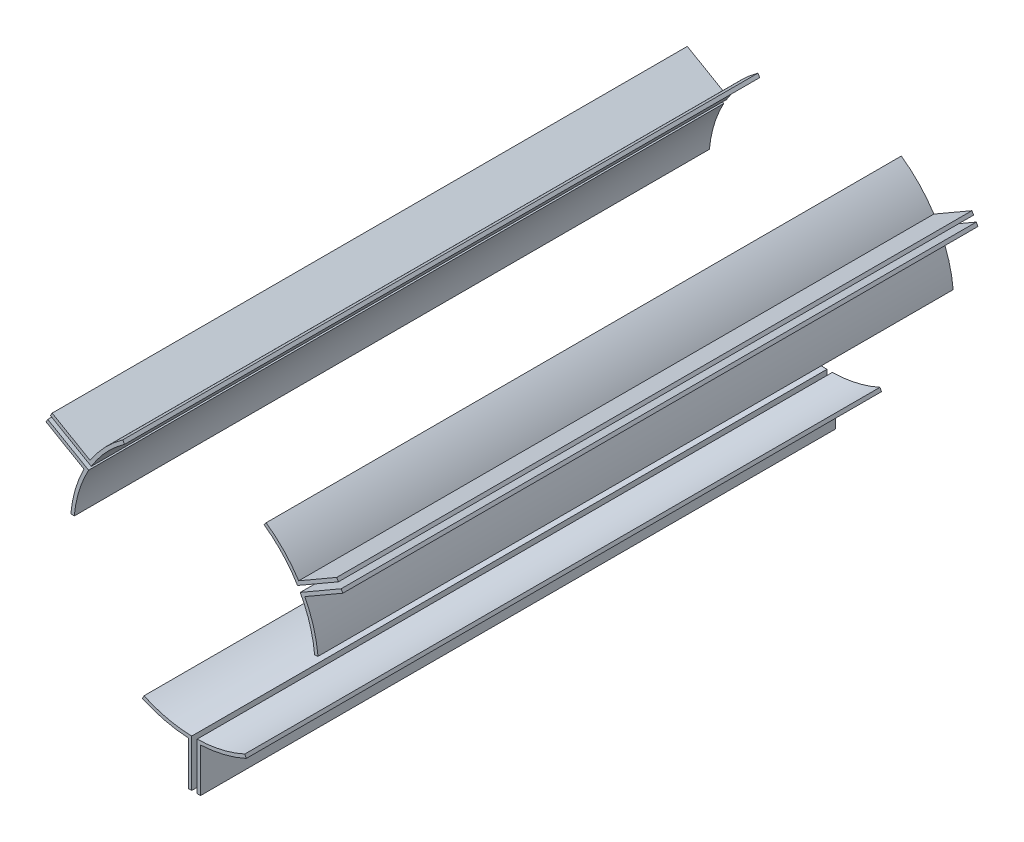
SolidWorks part; units mm, degrees
ref_plane "Front Plane" through (0, 0, 0) normal (0, 0, 1) x (1, 0, 0)
ref_plane "Top Plane" through (0, 0, 0) normal (0, 1, 0) x (1, 0, 0)
ref_plane "Right Plane" through (0, 0, 0) normal (1, 0, 0) x (0, 0, -1)
sketch "Sketch1" plane through (0, 0, 0) normal (0, 0, 1) x (1, 0, 0)
  line L0 (0, 0) -> (0, 104.0303) construction
  line L4 (0, 0) -> (35.2831, 76.7317) construction
  line L10 (0, 0) -> (129.8857, -74.9895) construction
  line L11 (0, 0) -> (-129.8857, -74.9895) construction
  line L28 (55, 0) -> (-55, 0) construction
  line L29 (0, 0) -> (0, -104.0303) construction
  line L30 (0, 0) -> (129.8857, 74.9895) construction
  line L31 (0, 0) -> (-129.8857, 74.9895) construction
  line L32 (-1.8796, -84.4341) -> (-1.8796, -117.4541)
  line L33 (-1.8796, -117.4541) -> (-4.2926, -117.4541)
  line L34 (-4.2926, -117.4541) -> (-4.2926, -86.7619)
  line L35 (-35.2831, -76.7317) -> (-36.2912, -78.924)
  line L56 (1.8796, -84.4341) -> (1.8796, -117.4541)
  line L57 (1.8796, -117.4541) -> (4.2926, -117.4541)
  line L58 (4.2926, -117.4541) -> (4.2926, -86.7619)
  line L59 (35.2831, -76.7317) -> (36.2912, -78.924)
  line L60 (-48.81, 68.9219) -> (-50.2046, 70.8911)
  line L61 (-99.5719, 62.4445) -> (-72.9917, 47.0984)
  line L62 (-100.7784, 60.3548) -> (-99.5719, 62.4445)
  line L63 (-72.1823, 43.8448) -> (-100.7784, 60.3548)
  line L64 (-74.0619, 40.5893) -> (-102.658, 57.0993)
  line L65 (-102.658, 57.0993) -> (-103.8645, 55.0095)
  line L66 (-103.8645, 55.0095) -> (-77.2843, 39.6634)
  line L67 (-84.0931, 7.8098) -> (-86.4958, 8.0329)
  line L68 (84.0931, 7.8098) -> (86.4958, 8.0329)
  line L69 (103.8645, 55.0095) -> (77.2843, 39.6634)
  line L70 (102.658, 57.0993) -> (103.8645, 55.0095)
  line L71 (74.0619, 40.5893) -> (102.658, 57.0993)
  line L72 (72.1823, 43.8448) -> (100.7784, 60.3548)
  line L73 (100.7784, 60.3548) -> (99.5719, 62.4445)
  line L74 (99.5719, 62.4445) -> (72.9917, 47.0984)
  line L75 (48.81, 68.9219) -> (50.2046, 70.8911)
  circle A0 centre (0, 0) radius 84.455 construction
  arc A13 (-1.8796, -84.4341) -> (-35.2831, -76.7317) centre (0, 0) cw
  arc A14 (-36.2912, -78.924) -> (-4.2926, -86.7619) centre (0, 0) ccw
  arc A25 (36.2912, -78.924) -> (4.2926, -86.7619) centre (0, 0) cw
  arc A26 (1.8796, -84.4341) -> (35.2831, -76.7317) centre (0, 0) ccw
  arc A27 (-72.1823, 43.8448) -> (-48.81, 68.9219) centre (0, 0) cw
  arc A28 (-50.2046, 70.8911) -> (-72.9917, 47.0984) centre (0, 0) ccw
  arc A29 (-86.4958, 8.0329) -> (-77.2843, 39.6634) centre (0, 0) cw
  arc A30 (-74.0619, 40.5893) -> (-84.0931, 7.8098) centre (0, 0) ccw
  arc A31 (74.0619, 40.5893) -> (84.0931, 7.8098) centre (0, 0) cw
  arc A32 (86.4958, 8.0329) -> (77.2843, 39.6634) centre (0, 0) ccw
  arc A33 (50.2046, 70.8911) -> (72.9917, 47.0984) centre (0, 0) cw
  arc A34 (72.1823, 43.8448) -> (48.81, 68.9219) centre (0, 0) ccw
  point P45 (0, 0)
  point P46 (-1.8796, -86.7619)
  point P49 (0, 0)
  dimension "D2" = 84.455
  dimension "D5" = 120
  dimension "D6" = 120
  dimension "D1" = 1.8796
  dimension "D3" = 2.413
  dimension "D4" = 2.413
  dimension "D7" = 33.02
  dimension "D9" = 24.694
  dimension "D8" = 3
extrude "Boss-Extrude1" add sketch "Sketch1" along normal mid plane 444.5
sketch "Sketch2" plane through (0, 0, 273.05) normal (0, 0, 1) x (1, 0, 0)
  line L0 (0, 0) -> (168.576, 0) construction
equation "\"FIN_CAN_OUTER_RADIUS\"=3.325"
equation "\"D2@Sketch1\"=\"FIN_CAN_OUTER_RADIUS\""
equation "\"BRACKET_THICKNESS\"=0.095"
equation "\"D4@Sketch1\"=\"BRACKET_THICKNESS\""
equation "\"D3@Sketch1\"=\"BRACKET_THICKNESS\""
equation "\"BRACKET_STRAIGHT_ARM_LENGTH\"= 1.3"
equation "\"BRACKET_GAP_DISTANCE\"= 0.148"
equation "\"D7@Sketch1\"=\"BRACKET_STRAIGHT_ARM_LENGTH\""
equation "\"D1@Sketch1\"=\"BRACKET_GAP_DISTANCE\"/2"
equation "\"BRACKET_ALIGNMENT\"=120"
equation "\"D5@Sketch1\"=\"BRACKET_ALIGNMENT\""
equation "\"BRACKET_CURVED_ARM_ARCLENGTH\"= 1.4"
equation "\"D9@Sketch1\"=((\"BRACKET_CURVED_ARM_ARCLENGTH\"+(\"BRACKET_GAP_DISTANCE\"/2))*360)/(2*pi*(\"FIN_CAN_OUTER_RADIUS\"+\"BRACKET_THICKNESS\"))"
equation "\"BRACKET_LENGTH\"= 17.5"
equation "\"D1@Boss-Extrude1\"=\"BRACKET_LENGTH\""
